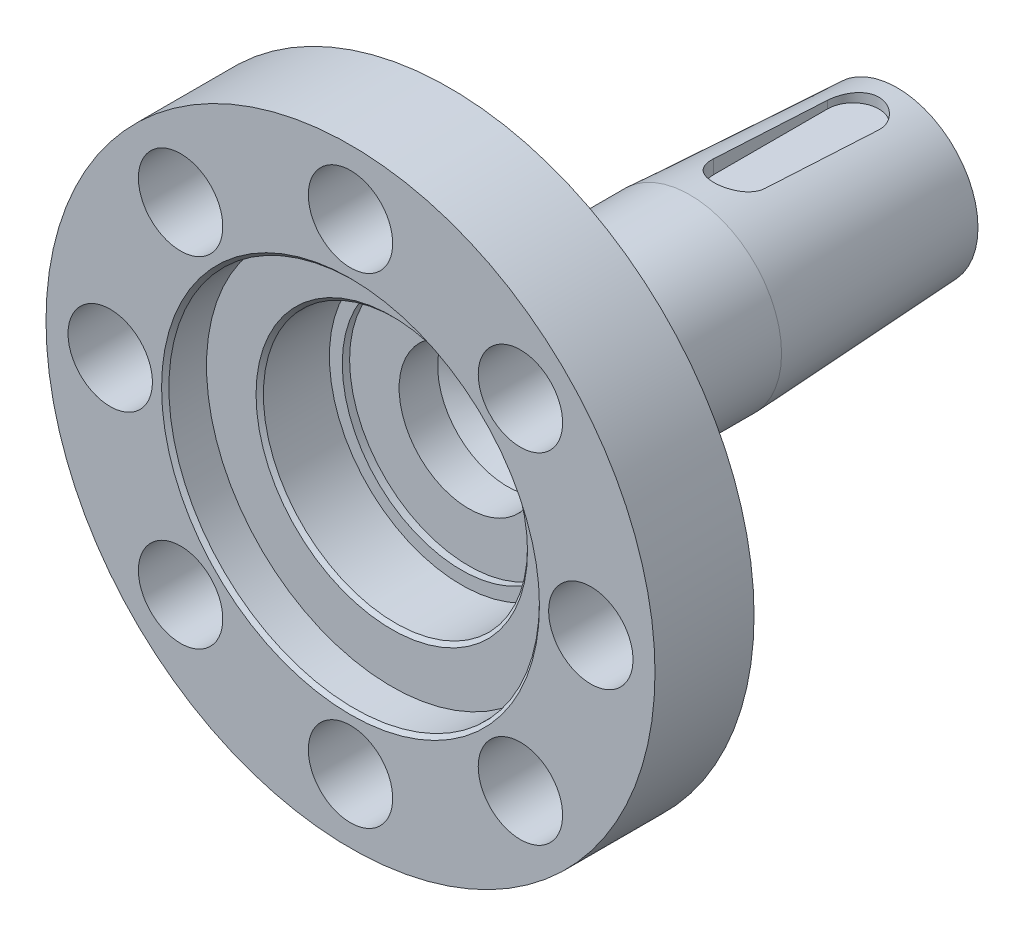
SolidWorks part; units mm, degrees
ref_plane "前视基准面" through (0, 0, 0) normal (0, 0, 1) x (1, 0, 0)
ref_plane "上视基准面" through (0, 0, 0) normal (0, 1, 0) x (1, 0, 0)
ref_plane "右视基准面" through (0, 0, 0) normal (1, 0, 0) x (0, 0, -1)
sketch "草图1" plane through (0, 0, 0) normal (1, 0, 0) x (0, 0, -1)
  line L0 (0, 0) -> (116.3605, 0) construction
  line L1 (55, 0) -> (-55, 0) construction
  line L2 (0, 0) -> (0, 83)
  line L3 (0, 55) -> (0, -55) construction
  line L4 (0, 83) -> (27, 83)
  line L5 (27, 83) -> (27, 53.6244)
  line L6 (27, 53.6244) -> (48, 41.5)
  line L7 (48, 41.5) -> (48, 30)
  line L8 (48, 30) -> (50.5, 30)
  line L9 (50.5, 30) -> (50.5, 25)
  line L10 (50.5, 25) -> (92.5, 25)
  line L11 (92.5, 25) -> (149, 22.039)
  line L12 (149, 22.039) -> (149, 0)
  line L13 (0, 0) -> (149, 0)
  point P5 (0, 0)
  dimension "D1" = 166
  dimension "D2" = 83
  dimension "D3" = 60
  dimension "D4" = 50
  dimension "D5" = 3
  dimension "D6" = 56.5
  dimension "D7" = 149
  dimension "D8" = 27
  dimension "D9" = 48
  dimension "D10" = 2.5
  dimension "D11" = 30
revolve "旋转1" add sketch "草图1" angle 360 about L0
hole_wizard "M20 螺纹孔1" positions "草图2" profile "草图3" tap size "M20" standard "GB"
sketch "草图2" plane through (0, 0, -149) normal (0, 0, -1) x (-1, 0, 0)
  point P0 (0, 0)
sketch "草图3" plane through (0, 0, -149) normal (1, 0, 0) x (0, 1, 0)
  line L0 (0, 0) -> (0, 40.2575)
  line L1 (0, 40.2575) -> (8.75, 35)
  line L2 (8.75, 35) -> (8.75, 1.275)
  line L3 (8.75, 1.275) -> (10.025, 0)
  line L5 (10.025, 0) -> (0, 0)
  line L6 (-8.75, 1.275) -> (-10.025, 0) construction
  line L10 (0, 40.2575) -> (-8.75, 35) construction
  line L11 (0, -6.35) -> (0, 107.95) construction
  dimension "螺纹孔钻头直径" = 17.5
  dimension "螺纹孔钻头深度" = 35
  dimension "近端锥形沉头孔直径" = 20.05
  dimension "近端锥形沉头孔角度" = 90
  dimension "导头角度" = 118
cosmetic thread "孔螺纹线1" parameters "D1"=30, "D2"=20
sketch "草图4" plane through (0, 0, 0) normal (0, 1, 0) x (1, 0, 0)
  line L0 (0, 137) -> (0, 106) construction
  line L1 (0, -81.95) -> (0, 81.95) construction
  line L2 (7, 137) -> (7, 106)
  line L3 (-7, 137) -> (-7, 106)
  line L4 (22.039, 149) -> (-22.039, 149) construction
  arc A0 (7, 137) -> (-7, 137) centre (0, 137) ccw
  arc A1 (-7, 106) -> (7, 106) centre (0, 106) ccw
  point P5 (0, 121.5)
  dimension "D2" = 45
  dimension "D3" = 5
  dimension "D1" = 14
extrude "切除-拉伸1" cut sketch "草图4" along normal through all from offset 19.5
sketch "草图5" plane through (0, 0, 0) normal (0, 0, 1) x (1, 0, 0)
  circle A0 centre (0, 0) radius 50.5
  dimension "D1" = 101
extrude "切除-拉伸2" cut sketch "草图5" against normal blind 11.25
sketch "草图6" plane through (0, 0, -11.25) normal (0, 0, 1) x (1, 0, 0)
  circle A0 centre (0, 0) radius 36
  dimension "D1" = 72
extrude "切除-拉伸3" cut sketch "草图6" against normal blind 19
sketch "草图7" plane through (0, 0, 0) normal (0, 0, 1) x (1, 0, 0)
  circle A0 centre (0, 0) radius 32.5
  dimension "D1" = 65
extrude "切除-拉伸4" cut sketch "草图7" against normal blind 32.25
chamfer "倒角1" distance 1 angle 45 2 edges at (36, 0, -11.25) (50.5, 0, 0)
sketch "草图8" plane through (0, 0, 0) normal (0, 0, 1) x (1, 0, 0)
  point P0 (0, 0)
hole_wizard "孔1" positions "草图8" profile "草图9" legacy
sketch "草图9" plane through (0, 0, 0) normal (1, 0, 0) x (0, -1, 0)
  line L0 (0, 0) -> (0, 54.1664)
  line L1 (0, 54.1664) -> (19, 42.75)
  line L2 (19, 42.75) -> (19, 0)
  line L4 (19, 0) -> (0, 0)
  line L6 (0, 54.1664) -> (-19, 42.75) construction
  line L7 (0, -4.2442) -> (0, 117.3081) construction
  dimension "直径" = 38
  dimension "深度" = 42.75
  dimension "导头角度" = 118
sketch "草图10" plane through (0, 0, -27) normal (0, 0, -1) x (-1, 0, 0)
  circle A0 centre (0, 0) radius 65.5 construction
  point P3 (0, 65.5)
  point P6 (46.3155, 46.3155)
  point P7 (65.5, 0)
  point P8 (46.3155, -46.3155)
  point P9 (0, -65.5)
  point P10 (-46.3155, -46.3155)
  point P11 (-65.5, 0)
  point P12 (-46.3155, 46.3155)
  dimension "D1" = 131
  dimension "D2" = 8
hole_wizard "孔2" positions "草图10" profile "草图11" legacy end condition through all
sketch "草图11" plane through (46.3155, 46.3155, -27) normal (1, 0, 0) x (0, 1, 0)
  line L0 (0, 0) -> (0, 27)
  line L1 (0, 27) -> (11.5, 27)
  line L2 (11.5, 27) -> (11.5, 0)
  line L3 (11.5, 0) -> (0, 0)
  line L4 (0, 110) -> (0, -10) construction
  dimension "直径" = 23
  dimension "深度" = 27
